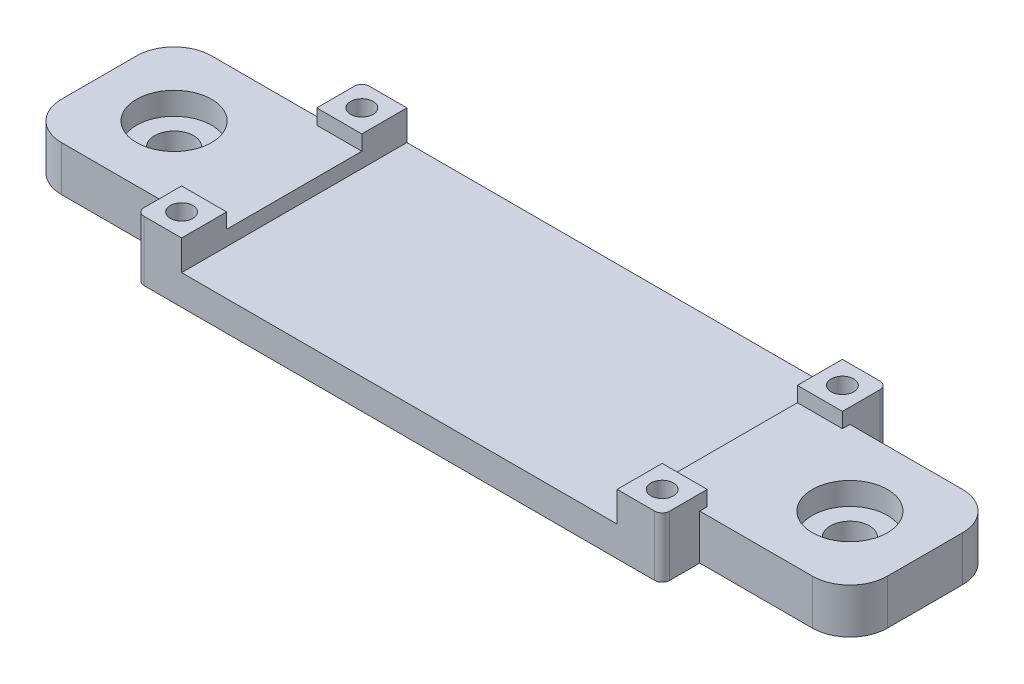
SolidWorks part; units mm, degrees
ref_plane "前视基准面" through (0, 0, 0) normal (0, 0, 1) x (1, 0, 0)
ref_plane "上视基准面" through (0, 0, 0) normal (0, 1, 0) x (1, 0, 0)
ref_plane "右视基准面" through (0, 0, 0) normal (1, 0, 0) x (0, 0, -1)
other "Configuration Table"
sketch "草图25" plane through (0, 0, 0) normal (0, 1, 0) x (1, 0, 0)
  line L5 (-35, -15) -> (35, -15)
  line L6 (-35, -15) -> (-35, 15)
  line L7 (-35, 15) -> (35, 15)
  line L8 (35, -15) -> (35, 15)
  circle A0 centre (-32, 12) radius 1.5
  circle A1 centre (32, 12) radius 1.5
  circle A2 centre (32, -12) radius 1.5
  circle A3 centre (-32, -12) radius 1.5
extrude "凸台-拉伸9" add sketch "草图25" along normal blind 4
sketch "草图26" plane through (0, 4, 0) normal (0, 1, 0) x (1, 0, 0)
  line L1 (-35, 15) -> (-29, 15)
  line L2 (-35, 15) -> (-35, 9)
  line L3 (-35, 9) -> (-29, 9)
  line L4 (-29, 15) -> (-29, 9)
  line L5 (-35, -15) -> (-29, -15)
  line L6 (-35, -15) -> (-35, -9)
  line L7 (-35, -9) -> (-29, -9)
  line L8 (-29, -15) -> (-29, -9)
  line L9 (35, -15) -> (29, -15)
  line L10 (35, -15) -> (35, -9)
  line L11 (35, -9) -> (29, -9)
  line L12 (29, -15) -> (29, -9)
  line L13 (35, 15) -> (29, 15)
  line L14 (35, 15) -> (35, 9)
  line L15 (35, 9) -> (29, 9)
  line L16 (29, 15) -> (29, 9)
  circle A0 centre (-32, 12) radius 1.5
  circle A1 centre (-32, -12) radius 1.5
  circle A2 centre (32, -12) radius 1.5
  circle A3 centre (32, 12) radius 1.5
extrude "凸台-拉伸10" add sketch "草图26" along normal blind 4
fillet "圆角3" radius 1 4 edges at (35, 4, -15) (35, 4, 15) (-35, 4, 15) (-35, 4, -15)
sketch "草图27" plane through (0, 0, 0) normal (0, -1, 0) x (1, 0, 0)
  line L0 (35, 14) -> (35, -14) construction
  line L1 (35, 0) -> (55, 0)
  line L2 (35, 0) -> (35, 10)
  line L3 (35, 10) -> (55, 10)
  line L4 (55, 0) -> (55, 10)
  line L5 (-35, -14) -> (-35, 14) construction
  line L6 (-35, 0) -> (-55, 0)
  line L7 (-35, 0) -> (-35, 10)
  line L8 (-35, 10) -> (-55, 10)
  line L9 (-55, 0) -> (-55, 10)
  line L11 (-35, 0) -> (-55, 0)
  line L12 (-35, 0) -> (-35, -10)
  line L13 (-35, -10) -> (-55, -10)
  line L14 (-55, 0) -> (-55, -10)
  line L15 (35, 0) -> (55, 0)
  line L16 (35, 0) -> (35, -10)
  line L17 (35, -10) -> (55, -10)
  line L18 (55, 0) -> (55, -10)
  circle A0 centre (-45, 0) radius 2.6
  circle A1 centre (45, 0) radius 2.6
  line M18 (35, -14) -> (35, 14)
  line M22 (-35, 14) -> (-35, -14)
extrude "凸台-拉伸11" add sketch "草图27" against normal blind 6 contours A0 L6 L8 L9 M22 | A0 L6 L14 L13 M22 | A1 L1 L4 L3 M18 | A1 L1 L17 L18 M18
sketch "草图28" plane through (0, 4, 0) normal (0, 1, 0) x (1, 0, 0)
  line L1 (-35, 9) -> (-29, 9)
  line L2 (-35, 9) -> (-35, -9)
  line L3 (-35, -9) -> (-29, -9)
  line L4 (-29, 9) -> (-29, -9)
  line L5 (29, 9) -> (35, 9)
  line L6 (29, 9) -> (29, -9)
  line L7 (29, -9) -> (35, -9)
  line L8 (35, 9) -> (35, -9)
extrude "凸台-拉伸12" add sketch "草图28" along normal blind 2
sketch "草图29" plane through (0, 6, 0) normal (0, 1, 0) x (1, 0, 0)
  circle A0 centre (-45, 0) radius 5
  circle A1 centre (45, 0) radius 5
extrude "切除-拉伸15" cut sketch "草图29" against normal blind 3
fillet "圆角4" radius 5 4 edges at (55, 3, 10) (55, 3, -10) (-55, 3, 10) (-55, 3, -10)
